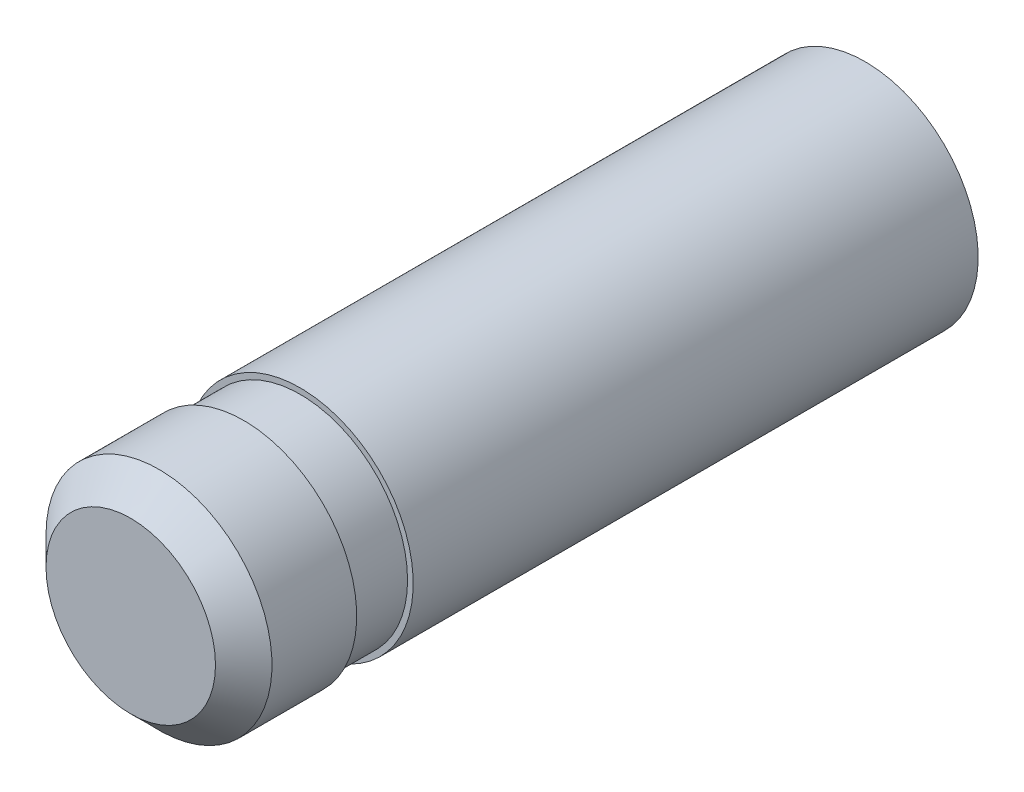
SolidWorks part; units mm, degrees
ref_plane "Front Plane" through (0, 0, 0) normal (0, 0, 1) x (1, 0, 0)
ref_plane "Top Plane" through (0, 0, 0) normal (0, 1, 0) x (1, 0, 0)
ref_plane "Right Plane" through (0, 0, 0) normal (1, 0, 0) x (0, 0, -1)
sketch "Sketch2" plane through (0, 0, 0) normal (0, 0, 1) x (1, 0, 0)
  circle A0 centre (0, 0) radius 2
  dimension "D1" = 4
extrude "Boss-Extrude1" add sketch "Sketch2" along normal blind 13
sketch "Sketch3" plane through (0, 0, 0) normal (0, 0, -1) x (-1, 0, 0)
  circle A0 centre (0, 0) radius 1.9
  dimension "D1" = 3.8
extrude "Cut-Extrude1" cut sketch "Sketch3" against normal blind 1 from offset 10 flip side to cut offset against normal yes
chamfer "Chamfer1" distance 0.5 angle 45 1 edges at (2, 0, 13)
